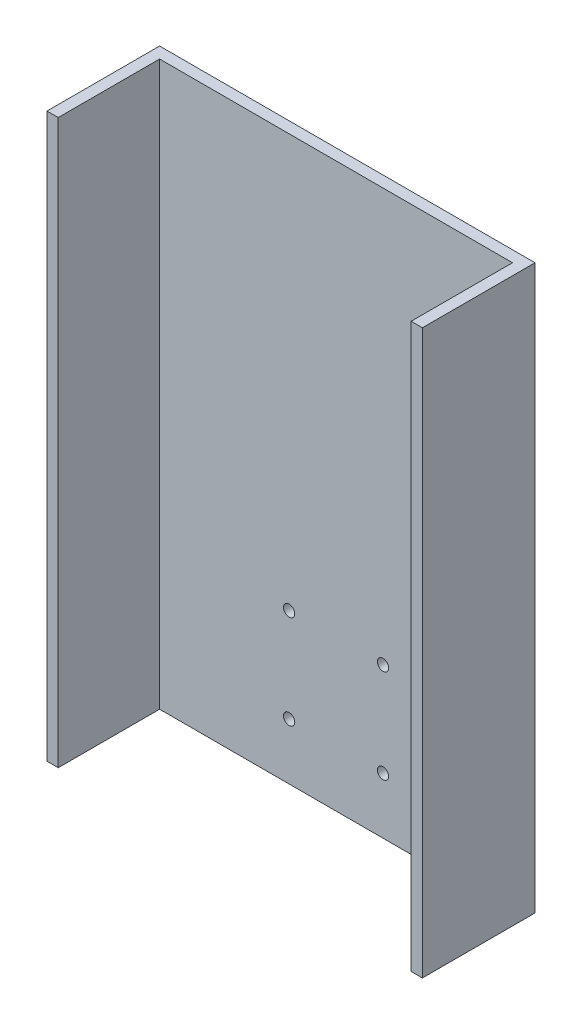
SolidWorks part; units mm, degrees
ref_plane "Front Plane" through (0, 0, 0) normal (0, 0, 1) x (1, 0, 0)
ref_plane "Top Plane" through (0, 0, 0) normal (0, 1, 0) x (1, 0, 0)
ref_plane "Right Plane" through (0, 0, 0) normal (1, 0, 0) x (0, 0, -1)
sketch "Sketch1" plane through (0, 0, 0) normal (0, 0, 1) x (1, 0, 0)
  line L1 (50, -75) -> (-50, -75)
  line L2 (50, -75) -> (50, 75)
  line L3 (50, 75) -> (-50, 75)
  line L4 (-50, -75) -> (-50, 75)
  line L5 (50, -75) -> (-50, 75) construction
  line L6 (50, 75) -> (-50, -75) construction
  point P0 (0, 0)
  dimension "D1" = 100
  dimension "D2" = 150
extrude "Boss-Extrude1" add sketch "Sketch1" along normal blind 30
shell "Shell1" thickness 3
sketch "Sketch2" plane through (0, 0, 3) normal (0, 0, 1) x (1, 0, 0)
  line L0 (0, -75) -> (0, 75) construction
  line L1 (50, 75) -> (47, 75) construction
  line L2 (-50, -75) -> (-47, -75) construction
  line L3 (-12.5, 75) -> (-12.5, -75) construction
  line L5 (-47, -75) -> (47, -75) construction
  line L6 (47, 75) -> (-47, 75) construction
  circle A0 centre (-12.5, -35) radius 1.5
  circle A1 centre (-12.5, -60) radius 1.5
  circle A2 centre (12.5, -60) radius 1.5
  circle A3 centre (12.5, -35) radius 1.5
  dimension "D1" = 3
  dimension "D2" = 25
  dimension "D3" = 25
  dimension "D4" = 15
  dimension "D5" = 12.5
  dimension "D6" = 25
extrude "Cut-Extrude2" cut sketch "Sketch2" against normal up to next
